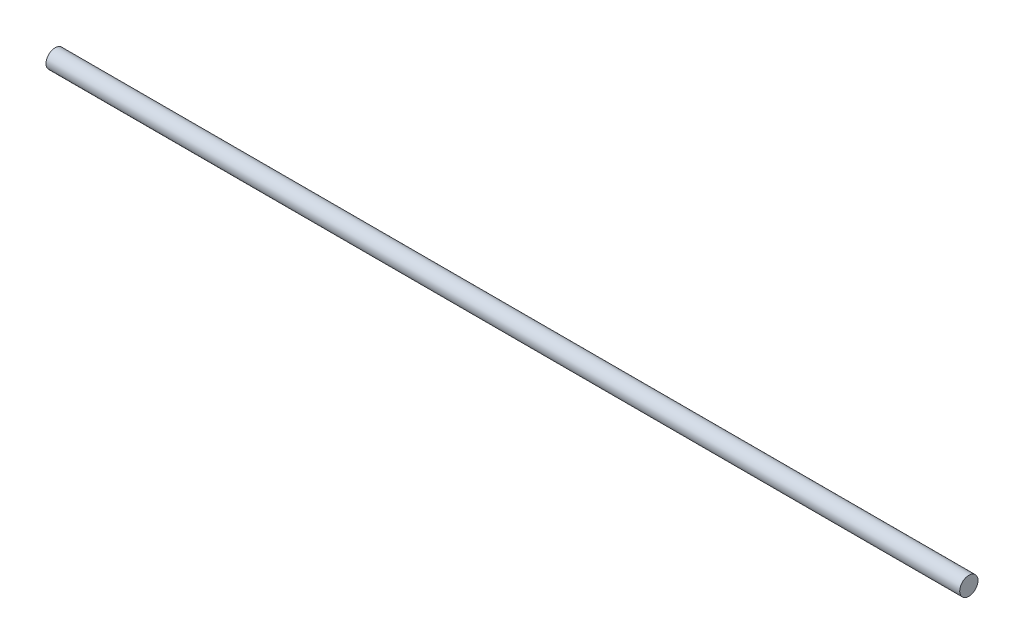
SolidWorks part; units mm, degrees
material "201 Annealed Stainless Steel (SS)"
ref_plane "Front Plane" through (0, 0, 0) normal (1, 0, 0) x (0, 1, 0)
ref_plane "Top Plane" through (0, 0, 0) normal (0, 0, 1) x (0, 1, 0)
ref_plane "Right Plane" through (0, 0, 0) normal (0, 1, 0) x (-1, 0, 0)
sketch "Sketch1" plane through (0, 0, 0) normal (1, 0, 0) x (0, 1, 0)
  circle A0 centre (0, 0) radius 1
  dimension "D1" = 2
extrude "Boss-Extrude1" add sketch "Sketch1" along normal mid plane 100
